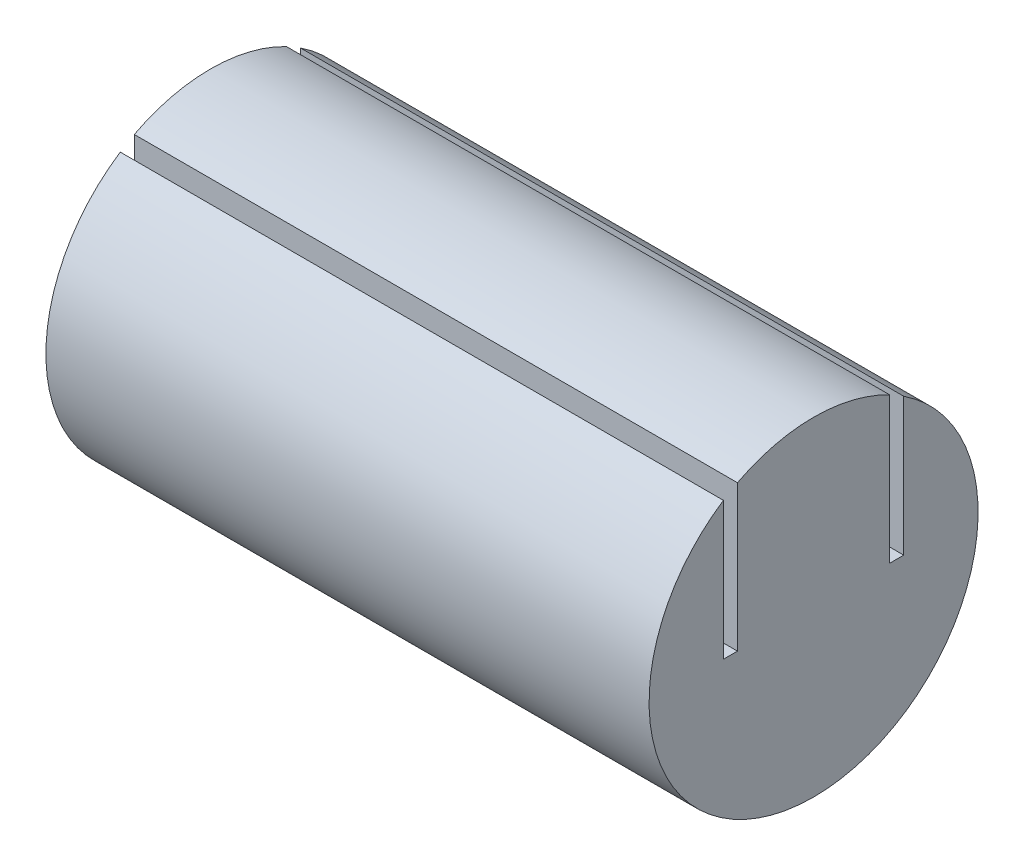
SolidWorks part; units mm, degrees
ref_plane "Front Plane" through (0, 0, 0) normal (0, 0, 1) x (1, 0, 0)
ref_plane "Top Plane" through (0, 0, 0) normal (0, 1, 0) x (1, 0, 0)
ref_plane "Right Plane" through (0, 0, 0) normal (1, 0, 0) x (0, 0, -1)
sketch "Sketch1" plane through (0, 0, 0) normal (1, 0, 0) x (0, 0, -1)
  line L0 (-4.4069, 0) -> (4.4069, 0) construction
  line L1 (-5.2197, 8.4442) -> (-4.4069, 8.4442)
  line L2 (-5.2197, 8.4442) -> (-5.2197, 0)
  line L3 (-5.2197, 0) -> (-4.4069, 0)
  line L4 (-4.4069, 8.4442) -> (-4.4069, 0)
  line L5 (4.4069, 0) -> (5.2197, 0)
  line L6 (4.4069, 0) -> (4.4069, 8.4442)
  line L7 (4.4069, 8.4442) -> (5.2197, 8.4442)
  line L8 (5.2197, 0) -> (5.2197, 8.4442)
  circle A0 centre (0, 0) radius 9.525
  point P11 (0, 0)
  point P12 (0, 0)
  point P13 (0, 0)
  dimension "D1" = 0.8128
  dimension "D3" = 19.05
  dimension "D2" = 8.8138
extrude "Boss-Extrude1" add sketch "Sketch1" along normal blind 34.925 contours L4 L0 L6 A0 | L0 L3 L2 A0 L8 L5
